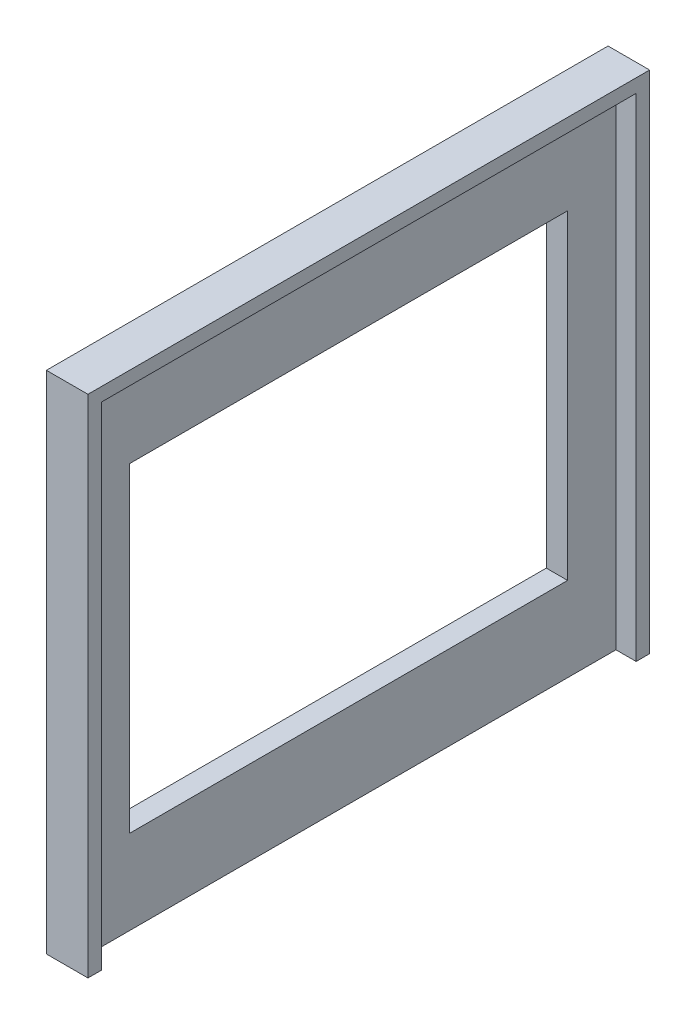
SolidWorks part; units mm, degrees
ref_plane "Front Plane" through (0, 0, 0) normal (0, 0, 1) x (1, 0, 0)
ref_plane "Top Plane" through (0, 0, 0) normal (0, 1, 0) x (1, 0, 0)
ref_plane "Right Plane" through (0, 0, 0) normal (1, 0, 0) x (0, 0, -1)
sketch "Sketch1" plane through (0, 0, 0) normal (1, 0, 0) x (0, 0, -1)
  line L1 (0, 0) -> (500, 0)
  line L2 (0, 0) -> (0, 450)
  line L3 (0, 450) -> (500, 450)
  line L4 (500, 0) -> (500, 450)
  line L5 (55, 360) -> (445, 360)
  line L6 (55, 360) -> (55, 75)
  line L7 (55, 75) -> (445, 75)
  line L8 (445, 360) -> (445, 75)
  dimension "D1" = 450
  dimension "D2" = 500
  dimension "D3" = 390
  dimension "D4" = 285
  dimension "D5" = 90
  dimension "D6" = 55
extrude "Boss-Extrude1" add sketch "Sketch1" along normal blind 19
sketch "Sketch2" plane through (19, 0, 0) normal (1, 0, 0) x (0, 0, -1)
  line L0 (500, 0) -> (500, 450) construction
  line L1 (0, 450) -> (500, 450)
  line L2 (0, 450) -> (0, 438)
  line L3 (0, 438) -> (500, 438)
  line L4 (500, 450) -> (500, 438)
  line L5 (0, 0) -> (500, 0) construction
  line L6 (0, 438) -> (12, 438)
  line L7 (0, 438) -> (0, 0)
  line L8 (0, 0) -> (12, 0)
  line L9 (12, 438) -> (12, 0)
  line L11 (500, 438) -> (488, 438)
  line L12 (500, 438) -> (500, 0)
  line L13 (500, 0) -> (488, 0)
  line L14 (488, 438) -> (488, 0)
  dimension "D1" = 12
extrude "Boss-Extrude4" add sketch "Sketch2" along normal blind 18 contours L7 L6 L9 L8
sketch "Sketch3" plane through (19, 0, 0) normal (1, 0, 0) x (0, 0, -1)
  line L0 (500, 0) -> (500, 450) construction
  line L1 (0, 450) -> (500, 450)
  line L2 (0, 450) -> (0, 438)
  line L3 (0, 438) -> (500, 438)
  line L4 (500, 450) -> (500, 438)
extrude "Boss-Extrude5" add sketch "Sketch3" along normal blind 18
sketch "Sketch4" plane through (19, 0, 0) normal (1, 0, 0) x (0, 0, -1)
  line L0 (500, 0) -> (500, 438) construction
  line L1 (500, 438) -> (488, 438)
  line L2 (500, 438) -> (500, 0)
  line L3 (500, 0) -> (488, 0)
  line L4 (488, 438) -> (488, 0)
  line L5 (12, 438) -> (500, 438) construction
  line L6 (12, 0) -> (500, 0) construction
extrude "Boss-Extrude6" add sketch "Sketch4" along normal blind 18
